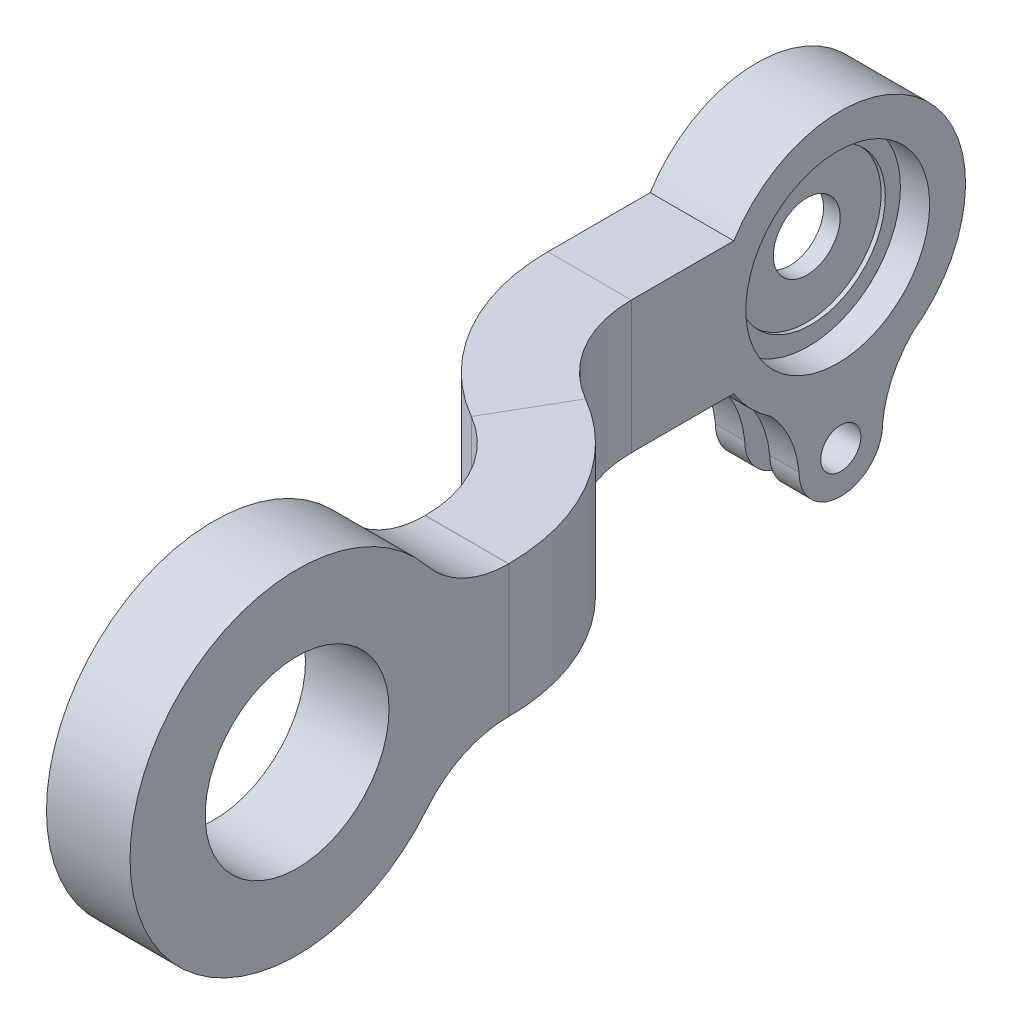
SolidWorks part; units mm, degrees
material "Resina de melamina"
ref_plane "Alzado" through (0, 0, 0) normal (0, 0, 1) x (1, 0, 0)
ref_plane "Planta" through (0, 0, 0) normal (0, 1, 0) x (1, 0, 0)
ref_plane "Vista lateral" through (0, 0, 0) normal (1, 0, 0) x (0, 0, -1)
sketch "Croquis1" plane through (0, 0, 0) normal (0, 1, 0) x (1, 0, 0)
  line L0 (0, 0) -> (0, 60) construction
  line L1 (0, 60) -> (-20, 60) construction
  line L2 (-20, 60) -> (-20, 85) construction
  line L3 (0, 15) -> (-20, 25.359) construction
  line L4 (-20, 85) -> (-20, 60)
  line L5 (0, 25.359) -> (0, 0)
  arc A0 (-20, 60) -> (-10, 42.6795) centre (0, 60) ccw
  arc A1 (0, 25.359) -> (-10, 42.6795) centre (-20, 25.359) ccw
  dimension "D4" = 20
  dimension "D1" = 60
  dimension "D2" = 25
  dimension "D3" = 20
sketch "Croquis2" plane through (0, 0, 0) normal (0, 0, 1) x (1, 0, 0)
  line L1 (5, -7.9175) -> (-5, -7.9175)
  line L2 (5, -7.9175) -> (5, 7.9175)
  line L3 (5, 7.9175) -> (-5, 7.9175)
  line L4 (-5, -7.9175) -> (-5, 7.9175)
  line L5 (5, -7.9175) -> (-5, 7.9175) construction
  line L6 (5, 7.9175) -> (-5, -7.9175) construction
  point P0 (0, 0)
  dimension "D1" = 10
sweep "Barrer1" add profiles "Croquis2" path "Croquis1"
sketch "Croquis4" plane through (-15, 0, 0) normal (1, 0, 0) x (0, 0, -1)
  line L1 (85, -7.9175) -> (85, 7.9175) construction
  circle A0 centre (85, 0) radius 15
  dimension "D2" = 30
extrude "Saliente-Extruir1" add sketch "Croquis4" against normal blind 10
sketch "Croquis5" plane through (5, 0, 0) normal (1, 0, 0) x (0, 0, -1)
  circle A0 centre (0, 0) radius 20
  dimension "D1" = 40
extrude "Saliente-Extruir2" add sketch "Croquis5" against normal blind 10
sketch "Croquis6" plane through (-15, 0, 0) normal (1, 0, 0) x (0, 0, -1)
  line L0 (60, 0) -> (85, 0) construction
  circle A0 centre (85, 0) radius 4
  dimension "D1" = 8
sketch "Croquis7" plane through (5, 0, 0) normal (1, 0, 0) x (0, 0, -1)
  circle A0 centre (0, 0) radius 11
  dimension "D1" = 22
ref_plane "Plano1" through (-15, 0, 0) normal (1, 0, 0) x (0, 0, -1)
sketch "Croquis12" plane through (-15, 0, 0) normal (1, 0, 0) x (0, 0, -1)
  line L0 (85.0685, -0.0274) -> (85.0685, 24.9726) construction
  line L1 (85.0685, 24.9726) -> (85.0685, 19.9726) construction
  line L2 (85.0685, 24.9726) -> (85.0685, 14.9726) construction
  arc A0 (90.0685, 19.9726) -> (80.0685, 19.9726) centre (85.0685, 19.9726) ccw
  arc A1 (94.2885, 11.6439) -> (75.8485, 11.6439) centre (85.0685, -0.0274) ccw
  spline S0 degree 2 poles (80.0685, 19.9726) (79.5667, 15.0283) (75.8485, 11.6439) knots 0 0 0 1 1 1
  spline S1 degree 2 poles (90.0685, 19.9726) (90.5703, 15.0283) (94.2885, 11.6439) knots 0 0 0 1 1 1
  dimension "D1" = 25
  dimension "D2" = 5
extrude "Saliente-Extruir5" add sketch "Croquis12" against normal blind 3.5
ref_plane "Plano2" through (-20, 0, 0) normal (1, 0, 0) x (0, 0, -1)
mirror "Simetría1" about plane through (-20, 0, 0) normal (1, 0, 0) of "Saliente-Extruir5"
sketch "Croquis13" plane through (-15, 0, 0) normal (1, 0, 0) x (0, 0, -1)
  circle A0 centre (85.0685, 19.9726) radius 2.5
  dimension "D1" = 5
extrude "Cortar-Extruir1" cut sketch "Croquis13" against normal blind 10
mirror "Simetría3" about plane through (0, 0, 0) normal (0, 1, 0) of "Simetría1", "Saliente-Extruir5"
sketch "Croquis20" plane through (-15, 0, 0) normal (1, 0, 0) x (0, 0, -1)
  line L0 (60, 0) -> (85, 0) construction
  line L2 (75.9168, 25.7358) -> (95.1724, 25.7358)
  line L3 (75.9168, 25.7358) -> (75.9168, 11.9372)
  line L5 (95.1724, 25.7358) -> (95.1724, 11.0237)
  arc A0 (95.1724, 11.0237) -> (75.9168, 11.9372) centre (85, 0) ccw
extrude "Cortar-Extruir5" cut sketch "Croquis20" against normal blind 10
sketch "Croquis21" plane through (-25, 0, 0) normal (-1, 0, 0) x (0, 0, 1)
  circle A0 centre (-85.0685, -19.9726) radius 2.4
  dimension "D1" = 4.8
extrude "Cortar-Extruir6" cut sketch "Croquis21" against normal blind 10
extrude "Cortar-Extruir7" cut sketch "Croquis7" against normal blind 10
fillet "Redondeo1" radius 12.5 1 edges at (0, -7.9175, -18.3661)
fillet "Redondeo2" radius 12.5 1 edges at (0, 7.9175, -18.3661)
sketch "Croquis22" plane through (-25, 0, 0) normal (-1, 0, 0) x (0, 0, 1)
  circle A0 centre (-85, 0) radius 11.5
  dimension "D1" = 23
extrude "Cortar-Extruir8" cut sketch "Croquis22" against normal blind 4
extrude "Cortar-Extruir9" cut sketch "Croquis6" against normal blind 8
sketch "Croquis23" plane through (-15, 0, 0) normal (1, 0, 0) x (0, 0, -1)
  circle A0 centre (84.7046, 0) radius 11
  dimension "D1" = 22
extrude "Cortar-Extruir10" cut sketch "Croquis23" against normal blind 4
sketch "Croquis24" plane through (-19, 0, 0) normal (1, 0, 0) x (0, 0, -1)
  circle A0 centre (85, 0) radius 11.2954
  circle A1 centre (85, 0) radius 8.9
  dimension "D1" = 17.8
extrude "Saliente-Extruir6" add sketch "Croquis24" along normal blind 0.5
sketch "Croquis25" plane through (-21, 0, 0) normal (-1, 0, 0) x (0, 0, 1)
  circle A0 centre (-85, 0) radius 11.5
  circle A1 centre (-85, 0) radius 8.9
  dimension "D1" = 17.8
extrude "Saliente-Extruir7" add sketch "Croquis25" along normal blind 0.5
equation "\"3.5.00mm\"=3"
